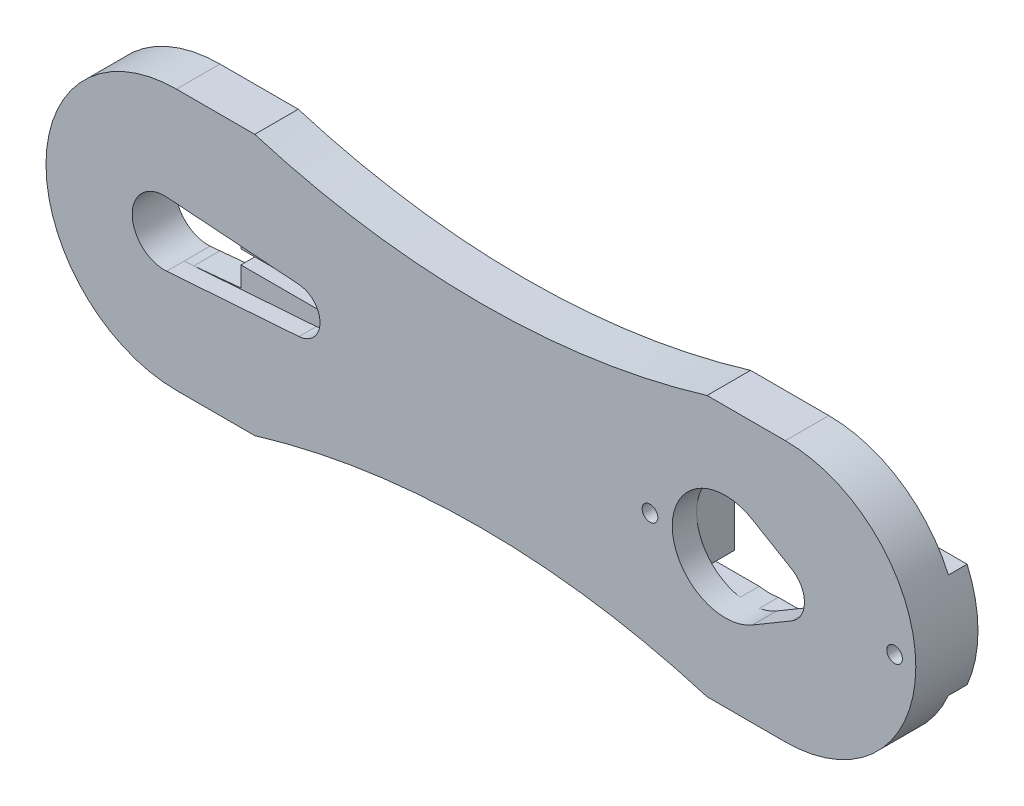
SolidWorks part; units mm, degrees
ref_plane "Front Plane" through (0, 0, 0) normal (0, 0, 1) x (1, 0, 0)
ref_plane "Top Plane" through (0, 0, 0) normal (0, 1, 0) x (1, 0, 0)
ref_plane "Right Plane" through (0, 0, 0) normal (1, 0, 0) x (0, 0, -1)
ref_plane "Plane1" through (0, 0, 0) normal (0, 0, -1) x (-1, 0, 0)
sketch "Sketch1" plane through (0, 0, 0) normal (0, 0, -1) x (-1, 0, 0)
  line L0 (-70, 0) -> (-61, 0)
  line L1 (0, 0) -> (-9, 0)
  line L2 (0, -15) -> (-10.6343, -15) construction
  line L3 (0, -30) -> (-9, -30)
  line L4 (-70, -30) -> (-61, -30)
  line L5 (0, -11.4) -> (-5.4, -11.905)
  line L6 (3.6, -15) -> (3.6, -20.4896) construction
  line L7 (0, -18.6) -> (-5.4, -18.095)
  line L8 (-5.4, -11.905) -> (-5.4, -18.095)
  arc A1 (-61, 0) -> (-9, 0) centre (-35, 86.1626) ccw
  arc A2 (-61, -30) -> (-9, -30) centre (-35, -116.1626) cw
  arc A9 (0, -11.4) -> (0, -18.6) centre (0, -15) cw
  arc A11 (-70, 0) -> (-70, -30) centre (-70, -15) ccw
  arc A15 (0, -30) -> (0, 0) centre (0, -15) ccw
  dimension "D1" = 7.2
  dimension "D2" = 9
  dimension "D3" = 90
  dimension "D4" = 9
  dimension "D5" = 6.19
  dimension "D10" = 15
  dimension "D11" = 100
extrude "Boss-Extrude1" add sketch "Sketch1" against normal blind 5
sketch "Croquis1" plane through (0, 0, 5) normal (0, 0, 1) x (1, 0, 0)
  line L0 (-1.1238, -11.3096) -> (14.0871, -12.4067)
  line L1 (14.0871, -17.5933) -> (-1.1238, -18.6904)
  circle A0 centre (0, -15) radius 3.6 construction
  arc A1 (14.0871, -12.4067) -> (14.0871, -17.5933) centre (13.9, -15) cw
  circle A2 centre (0, -15) radius 3.6
  arc A4 (-1.1238, -11.3096) -> (-1.1238, -18.6904) centre (-1.39, -15) ccw
  dimension "D1" = 2.6
  dimension "D2" = 16.5
  dimension "D3" = 3.7
sketch "Croquis3" plane through (0, 0, 0) normal (0, 0, -1) x (-1, 0, 0)
  line L1 (-80, -9) -> (-57, -9)
  line L2 (-80, -9) -> (-80, -21)
  line L3 (-80, -21) -> (-57, -21)
  line L4 (-57, -9) -> (-57, -21)
  arc A0 (0, -30) -> (0, 0) centre (0, -15) ccw construction
  arc A5 (-70, 0) -> (-70, -30) centre (-70, -15) ccw construction
  point P7 (15, -15)
  point P8 (-57, -15)
  dimension "D1" = 23
  dimension "D2" = 12
  dimension "D3" = 5
extrude "Cortar-Extruir2" cut sketch "Croquis3" against normal blind 2.2
sketch "Croquis4" plane through (0, 0, 2.2) normal (0, 0, -1) x (-1, 0, 0)
  line L0 (-66.2, -9.7464) -> (-70.7246, -12.4163)
  line L1 (-66.2, -20.2536) -> (-70.7246, -17.5837)
  line L2 (-57, -21) -> (-57, -9) construction
  arc A1 (-66.2, -20.2536) -> (-66.2, -9.7464) centre (-63.1, -15) ccw
  arc A3 (-70.7246, -12.4163) -> (-70.7246, -17.5837) centre (-69.2, -15) ccw
  point P12 (-57, -15)
  dimension "D1" = 3
  dimension "D2" = 12.2
  dimension "D4" = 15.2
extrude "Cortar-Extruir3" cut sketch "Croquis4" against normal through all both and the other way through all
sketch "Croquis6" [suppressed] plane through (0, 0, 2.2) normal (0, 0, -1) x (-1, 0, 0)
  circle A0 centre (-52.5, -20.715) radius 1.5
  arc A2 (-66.2, -20.2536) -> (-64.2, -21) centre (-63.1, -15) ccw construction
  circle A3 centre (-78.7, -15) radius 1.5
  arc A4 (-70.7246, -12.4163) -> (-70.7246, -17.5837) centre (-69.2, -15) ccw construction
  point P11 (-65.2329, -20.715)
  point P12 (-72.2, -15)
  dimension "D1" = 3
  dimension "D2" = 5
  dimension "D3" = 3
  dimension "D4" = 3
sketch "Sketch2" [suppressed] plane through (0, 0, 5) normal (0, 0, 1) x (1, 0, 0)
  line L1 (88.7475, -39.7589) -> (19.0099, -39.7589)
  line L2 (88.7475, -39.7589) -> (88.7475, 9.9653)
  line L3 (88.7475, 9.9653) -> (19.0099, 9.9653)
  line L4 (19.0099, -39.7589) -> (19.0099, 9.9653)
  line L5 (88.7475, -39.7589) -> (19.0099, 9.9653) construction
  line L6 (88.7475, 9.9653) -> (19.0099, -39.7589) construction
  point P0 (53.8787, -14.8968)
extrude "Cut-Extrude1" [suppressed] cut sketch "Sketch2" against normal through all both and the other way through all
sketch "Sketch3" [suppressed] plane through (0, 0, 5) normal (0, 0, 1) x (1, 0, 0)
  line L1 (42.9651, -39.6558) -> (-20.3981, -39.6558)
  line L2 (42.9651, -39.6558) -> (42.9651, 7.1799)
  line L3 (42.9651, 7.1799) -> (-20.3981, 7.1799)
  line L4 (-20.3981, -39.6558) -> (-20.3981, 7.1799)
  line L5 (42.9651, -39.6558) -> (-20.3981, 7.1799) construction
  line L6 (42.9651, 7.1799) -> (-20.3981, -39.6558) construction
  point P0 (11.2835, -16.2379)
extrude "Cut-Extrude2" [suppressed] cut sketch "Sketch3" against normal through all both and the other way through all
sketch "Sketch4" plane through (0, 0, 0) normal (0, 0, -1) x (-1, 0, 0)
  line L0 (-64.2, -9) -> (-80, -9) construction
  line L1 (-56, -22) -> (-81, -22)
  line L2 (-56, -22) -> (-56, -8)
  line L3 (-56, -8) -> (-81, -8)
  line L4 (-81, -22) -> (-81, -8)
  line L5 (-56, -22) -> (-81, -8) construction
  line L6 (-56, -8) -> (-81, -22) construction
  line L7 (-80, -9) -> (-80, -21) construction
  line L8 (-57, -21) -> (-57, -9) construction
  line L9 (-80, -21) -> (-64.2, -21) construction
  point P0 (-68.5, -15)
  dimension "D1" = 1
  dimension "D2" = 1
  dimension "D3" = 1
  dimension "D4" = 1
extrude "Cut-Extrude3" [suppressed] cut sketch "Sketch4" against normal through all both and the other way through all flip side to cut
sketch "Sketch6" plane through (0, 0, 5) normal (0, 0, 1) x (1, 0, 0)
  line L2 (14.0871, -12.4067) -> (-1.1238, -11.3096)
  line L3 (-1.1238, -18.6904) -> (14.0871, -17.5933)
  line L4 (14.0871, -12.4067) -> (-1.1238, -11.3096)
  line L5 (-1.1238, -18.6904) -> (14.0871, -17.5933)
  arc A4 (14.0871, -17.5933) -> (14.0871, -12.4067) centre (13.9, -15) ccw
  arc A5 (-1.1238, -11.3096) -> (-1.1238, -18.6904) centre (-1.39, -15) ccw
  arc A6 (14.0871, -17.5933) -> (14.0871, -12.4067) centre (13.9, -15) ccw
  arc A7 (-1.1238, -11.3096) -> (-1.1238, -18.6904) centre (-1.39, -15) ccw
  dimension "D2" = 0
extrude "Cut-Extrude4" cut sketch "Sketch6" against normal blind 2 and the other way through all
sketch "Sketch7" plane through (0, 0, 5) normal (0, 0, 1) x (1, 0, 0)
  line L1 (17.0468, -20.0398) -> (-5.5875, -20.0398)
  line L2 (17.0468, -20.0398) -> (17.0468, -10.2872)
  line L3 (17.0468, -10.2872) -> (-5.5875, -10.2872)
  line L4 (-5.5875, -20.0398) -> (-5.5875, -10.2872)
  line L5 (17.0468, -20.0398) -> (-5.5875, -10.2872) construction
  line L6 (17.0468, -10.2872) -> (-5.5875, -20.0398) construction
  point P0 (5.7297, -15.1635)
extrude "Cut-Extrude5" [suppressed] cut sketch "Sketch7" against normal through all flip side to cut
sketch "Sketch8" plane through (0, 0, 3) normal (0, 0, 1) x (1, 0, 0)
  line L0 (-1.1238, -11.3096) -> (0, -11.4)
  line L1 (-1.1238, -18.6904) -> (0, -18.6)
  arc A0 (0, -11.4) -> (0, -18.6) centre (0, -15) ccw construction
  arc A1 (0, -11.4) -> (0, -18.6) centre (0, -15) ccw
  arc A2 (-1.1238, -11.3096) -> (-1.1238, -18.6904) centre (-1.39, -15) ccw construction
  arc A3 (-1.1238, -11.3096) -> (-1.1238, -18.6904) centre (-1.39, -15) ccw
extrude "Cut-Extrude6" cut sketch "Sketch8" against normal through all
sketch "Sketch9" plane through (0, 0, 0) normal (0, 0, -1) x (-1, 0, 0)
  line L0 (-80, -21) -> (-64.2, -21) construction
  line L1 (-83.7477, -21) -> (-80, -21)
  line L3 (-83.7477, -9) -> (-80, -9)
  line L4 (-80, -21) -> (-80, -9)
  line L7 (-80, -15) -> (-57, -15) construction
  line L8 (-68.5, -15) -> (-68.5, -4.7031) construction
  line L9 (-52, -9) -> (-57, -9)
  line L10 (-57, -21) -> (-57, -9)
  line L11 (-52, -21) -> (-57, -21)
  line L12 (-52, -21) -> (-52, -9)
  arc A0 (-57, -15) -> (-62, -9) centre (-63.1, -15) ccw construction
  arc A1 (-70, 0) -> (-70, -30) centre (-70, -15) ccw construction
  arc A2 (-83.7477, -9) -> (-83.7477, -21) centre (-70, -15) ccw
  dimension "D1" = 5
extrude "Boss-Extrude2" add sketch "Sketch9" along normal blind 2.15
sketch "Sketch10" plane through (0, 0, -2.15) normal (0, 0, -1) x (-1, 0, 0)
  line L0 (-80, -15) -> (-57, -15) construction
  line L1 (-80, -9) -> (-80, -21) construction
  line L2 (-57, -9) -> (-57, -21) construction
  line L3 (-68.5, -15) -> (-68.5, -4.9258) construction
  circle A0 centre (-54.44, -15) radius 0.9
  circle A1 centre (-54.44, -15) radius 2.56 construction
  circle A2 centre (-82.56, -15) radius 0.9
  dimension "D1" = 1.8
  dimension "D2" = 5.12
extrude "Cut-Extrude7" cut sketch "Sketch10" against normal blind 8
sketch "Sketch11" plane through (0, 0, 3) normal (0, 0, 1) x (1, 0, 0)
  line L0 (5.4, -14.2) -> (14.9, -14.2)
  line L1 (14.9, -15.8) -> (5.4, -15.8)
  line L2 (5.4, -15.8) -> (5.4, -14.2)
  line L3 (5.4, -15) -> (-5.09, -15) construction
  line L4 (5.4, -11.905) -> (5.4, -18.095) construction
  line L5 (15.7, -15) -> (16.5, -15) construction
  circle A0 centre (14.9, -15) radius 0.8 construction
  arc A1 (-1.1238, -11.3096) -> (-1.1238, -18.6904) centre (-1.39, -15) ccw construction
  circle A4 centre (5.4, -15) radius 0.8 construction
  arc A5 (14.9, -14.2) -> (14.9, -15.8) centre (14.9, -15) cw
  circle A6 centre (8.5667, -15) radius 0.8 construction
  circle A7 centre (11.7333, -15) radius 0.8 construction
  arc A15 (14.0871, -17.5933) -> (14.0871, -12.4067) centre (13.9, -15) ccw construction
  dimension "D1" = 1.6
  dimension "D2" = 0.8
  dimension "D3" = 4
extrude "Cut-Extrude8" cut sketch "Sketch11" against normal through all
sketch "Sketch13" plane through (0, 0, -2.15) normal (0, 0, -1) x (-1, 0, 0)
  line L1 (-85.2369, -21.9119) -> (-51.6091, -21.9119)
  line L2 (-85.2369, -21.9119) -> (-85.2369, -8.3976)
  line L3 (-85.2369, -8.3976) -> (-51.6091, -8.3976)
  line L4 (-51.6091, -21.9119) -> (-51.6091, -8.3976)
extrude "Cut-Extrude9" [suppressed] cut sketch "Sketch13" against normal through all flip side to cut
sketch "Sketch14" plane through (0, 0, 5) normal (0, 0, 1) x (1, 0, 0)
  line L1 (17.0783, -20.3657) -> (-5.4547, -20.3657)
  line L2 (17.0783, -20.3657) -> (17.0783, -9.866)
  line L3 (17.0783, -9.866) -> (-5.4547, -9.866)
  line L4 (-5.4547, -20.3657) -> (-5.4547, -9.866)
  line L5 (17.0783, -20.3657) -> (-5.4547, -9.866) construction
  line L6 (17.0783, -9.866) -> (-5.4547, -20.3657) construction
  point P0 (5.8118, -15.1159)
extrude "Cut-Extrude10" [suppressed] cut sketch "Sketch14" against normal through all flip side to cut
equation "\"D1@Sketch4\"=\"D3@Sketch4\""
equation "\"D3@Sketch4\"=\"D4@Sketch4\""
equation "\"D2@Sketch4\"=\"D4@Sketch4\""
